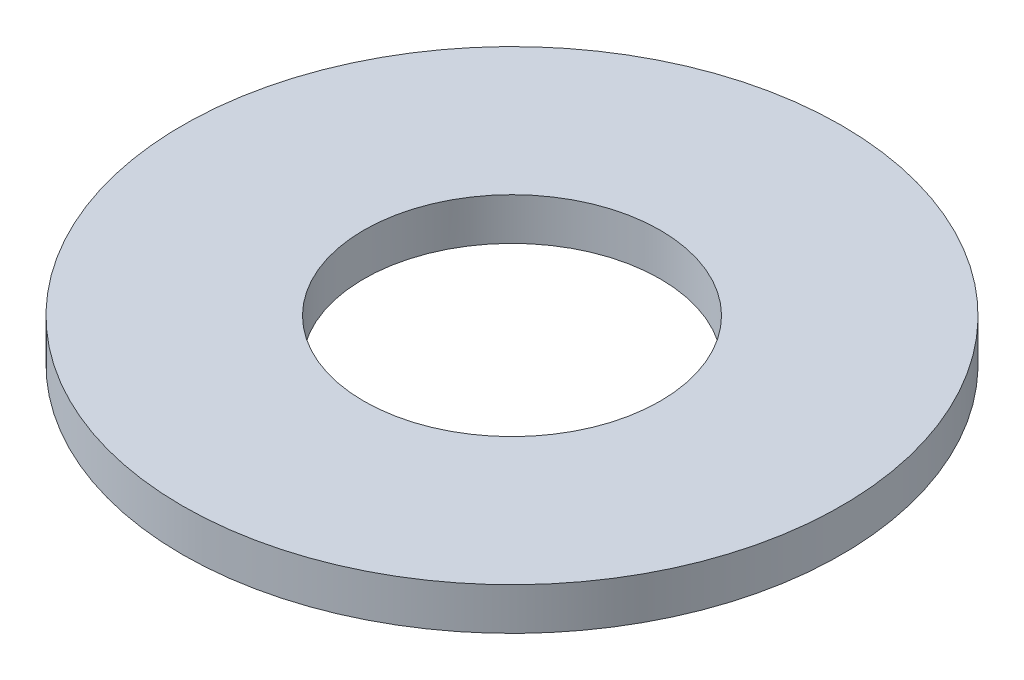
SolidWorks part; units mm, degrees
ref_plane "Front Plane" through (0, 0, 0) normal (0, 0, 1) x (1, 0, 0)
ref_plane "Top Plane" through (0, 0, 0) normal (0, 1, 0) x (1, 0, 0)
ref_plane "Right Plane" through (0, 0, 0) normal (1, 0, 0) x (0, 0, -1)
sketch "Sketch1" plane through (0, 0, 0) normal (0, 1, 0) x (1, 0, 0)
  circle A0 centre (0, 0) radius 15.875
  circle A1 centre (0, 0) radius 7.1374
extrude "Boss-Extrude2" add sketch "Sketch1" along normal blind 2.032 contours A0
sketch "Sketch3" plane through (0, 0, 0) normal (0, -1, 0) x (-1, 0, 0)
  circle A0 centre (0, 0) radius 7.1374
extrude "Cut-Extrude1" cut sketch "Sketch3" against normal blind 3.302 contours A0
